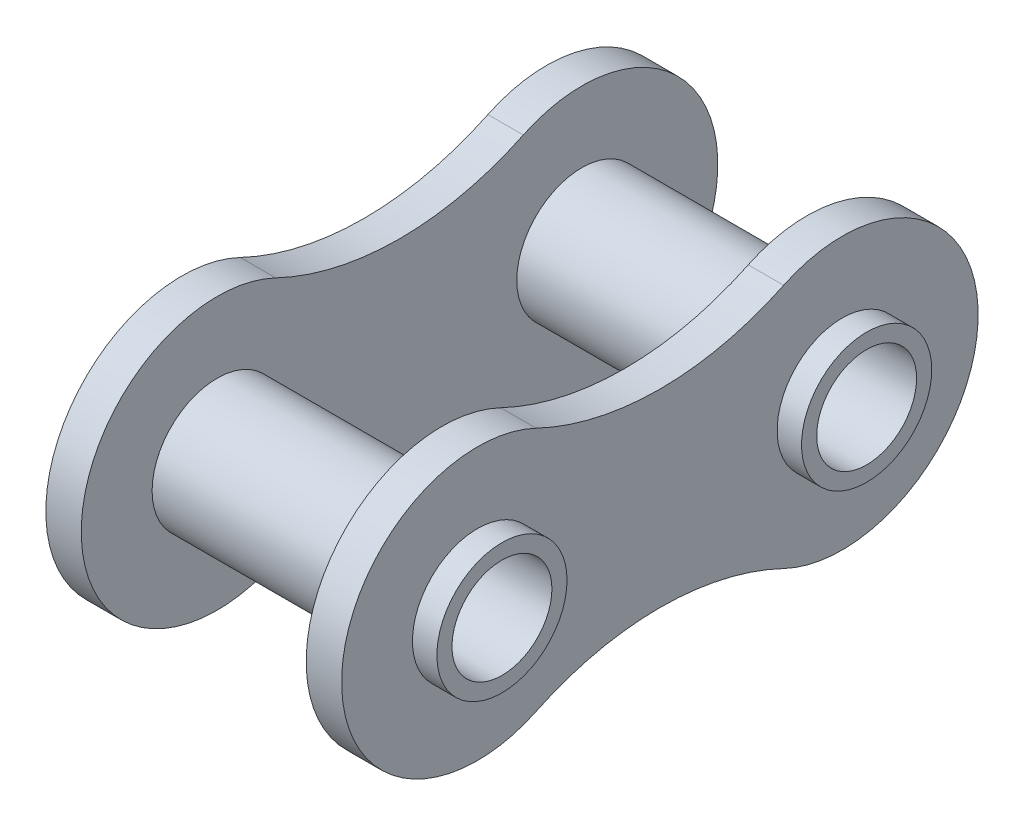
SolidWorks part; units mm, degrees
material "AISI 304"
ref_plane "Спереди" through (0, 0, 0) normal (0, 0, 1) x (1, 0, 0)
ref_plane "Сверху" through (0, 0, 0) normal (0, 1, 0) x (1, 0, 0)
ref_plane "Справа" through (0, 0, 0) normal (1, 0, 0) x (0, 0, -1)
other "Configuration Table"
sketch "Эскиз1" plane through (0, 0, 0) normal (1, 0, 0) x (0, 0, -1)
  line L0 (-19.05, 0) -> (19.05, 0) construction
  circle A0 centre (19.05, 0) radius 5.22
  circle A1 centre (-19.05, 0) radius 5.22
  circle A2 centre (-19.05, 0) radius 6.8
  circle A3 centre (19.05, 0) radius 6.8
  point P4 (0, 0)
  dimension "D2" = 13.6
  dimension "D3" = 10.44
  dimension "D1" = 38.1
extrude "Бобышка-Вытянуть1" add sketch "Эскиз1" along normal mid plane 36
sketch "Эскиз3" plane through (0, 0, 0) normal (1, 0, 0) x (0, 0, -1)
  line L0 (0, 50) -> (0, -50) construction
  circle A0 centre (-19.05, 0) radius 6.8
  circle A1 centre (19.05, 0) radius 6.8
  circle A2 centre (-19.05, 0) radius 6.8 construction
  arc A3 (-12.9299, 12.8134) -> (-12.9299, -12.8134) centre (-19.05, 0) ccw
  arc A4 (12.9299, -12.8134) -> (12.9299, 12.8134) centre (19.05, 0) ccw
  arc A5 (-12.9299, 12.8134) -> (12.9299, 12.8134) centre (0, 39.8841) ccw
  arc A6 (12.9299, -12.8134) -> (-12.9299, -12.8134) centre (0, -39.8841) ccw
  dimension "D1" = 28.4
  dimension "D2" = 60
extrude "Бобышка-Вытянуть3" add sketch "Эскиз3" along normal blind 3.7 from offset 11.75
mirror "Зеркальное отражение1" about plane through (0, 0, 0) normal (1, 0, 0) of "Бобышка-Вытянуть3"
ref_point "Точка1"
ref_point "Точка2"
